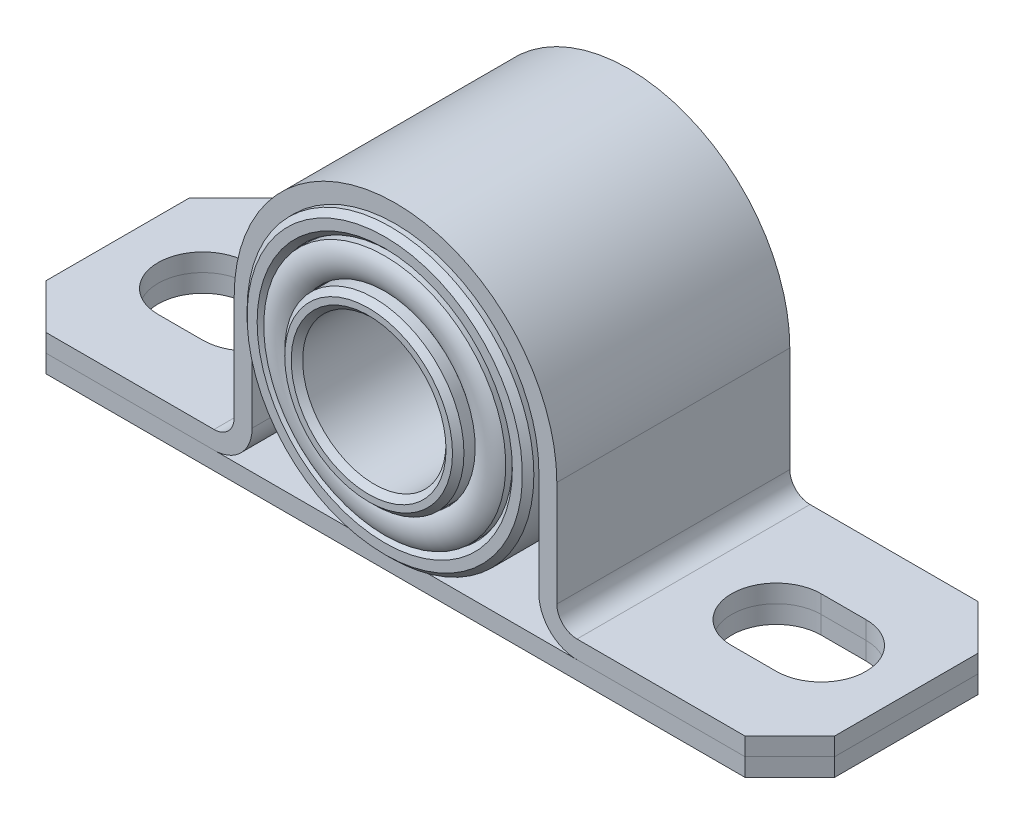
SolidWorks part; units mm, degrees
ref_plane "Front" through (0, 0, 0) normal (0, 0, 1) x (1, 0, 0)
ref_plane "Top" through (0, 0, 0) normal (0, 1, 0) x (1, 0, 0)
ref_plane "Right" through (0, 0, 0) normal (1, 0, 0) x (0, 0, -1)
sketch "Sketch1" plane through (0, 0, 0) normal (0, 1, 0) x (1, 0, 0)
  line L0 (-34.925, -10.3188) -> (34.925, 10.3187) construction
  line L1 (-34.925, -10.3188) -> (34.925, -10.3188)
  line L2 (-34.925, -10.3188) -> (-34.925, 10.3187)
  line L3 (-34.925, 10.3187) -> (34.925, 10.3187)
  line L4 (34.925, -10.3188) -> (34.925, 10.3187)
  line L5 (-27.3844, 0) -> (-23.4156, 0) construction
  line L6 (-23.4156, 0) -> (23.4156, 0) construction
  line L7 (23.4156, 0) -> (27.3844, 0) construction
  line L8 (-27.3844, -3.9688) -> (-23.4156, -3.9688)
  line L9 (23.4156, -3.9688) -> (27.3844, -3.9688)
  line L10 (-27.3844, 3.9688) -> (-23.4156, 3.9688)
  line L11 (23.4156, 3.9688) -> (27.3844, 3.9688)
  arc A0 (-27.3844, -3.9688) -> (-27.3844, 3.9688) centre (-27.3844, 0) cw
  arc A1 (-23.4156, -3.9688) -> (-23.4156, 3.9688) centre (-23.4156, 0) ccw
  arc A2 (23.4156, -3.9688) -> (23.4156, 3.9688) centre (23.4156, 0) cw
  arc A3 (27.3844, -3.9688) -> (27.3844, 3.9688) centre (27.3844, 0) ccw
  point P19 (-25.4, -3.9688)
  point P20 (25.4, -3.9688)
  dimension "Overall Length" = 69.85
  dimension "Mount Width" = 20.6375
  dimension "Hole Width" = 7.9375
  dimension "Hole Length" = 11.9062
  dimension "Hole Centers" = 50.8
extrude "Extrude1" add sketch "Sketch1" along normal blind 1.5875
sketch "Sketch2" plane through (0, 0, 0) normal (0, 0, 1) x (1, 0, 0)
  line L0 (-34.925, 1.5875) -> (-16.0734, 1.5875)
  line L1 (-12.7, 4.9609) -> (-12.7, 14.2875)
  line L2 (12.7, 14.2875) -> (12.7, 4.9609)
  line L3 (16.0734, 1.5875) -> (34.925, 1.5875)
  line L6 (-34.925, 1.5875) -> (-34.925, 3.175)
  line L7 (-34.925, 3.175) -> (-16.0734, 3.175)
  line L8 (-14.2875, 4.9609) -> (-14.2875, 14.2875)
  line L9 (14.2875, 14.2875) -> (14.2875, 4.9609)
  line L10 (16.0734, 3.175) -> (34.925, 3.175)
  line L11 (34.925, 3.175) -> (34.925, 1.5875)
  line L12 (-34.925, 1.5875) -> (-34.925, 0) construction
  line L13 (34.925, 1.5875) -> (34.925, 0) construction
  line L14 (-34.925, 1.5875) -> (34.925, 1.5875) construction
  line L15 (0, 0) -> (0, 28.575) construction
  line L16 (0, 28.575) -> (62.3285, 28.575) construction
  arc A0 (-12.7, 14.2875) -> (12.7, 14.2875) centre (0, 14.2875) cw
  arc A1 (-14.2875, 14.2875) -> (14.2875, 14.2875) centre (0, 14.2875) cw
  arc A2 (14.2875, 4.9609) -> (16.0734, 3.175) centre (16.0734, 4.9609) ccw
  arc A3 (-14.2875, 4.9609) -> (-16.0734, 3.175) centre (-16.0734, 4.9609) cw
  arc A4 (-12.7, 4.9609) -> (-16.0734, 1.5875) centre (-16.0734, 4.9609) cw
  arc A5 (12.7, 4.9609) -> (16.0734, 1.5875) centre (16.0734, 4.9609) ccw
  dimension "D2" = 1.7859
  dimension "Height" = 28.575
  dimension "Center" = 14.2875
extrude "Extrude2" add sketch "Sketch2" along normal up to surface and the other way up to surface separate body up to face at (0, 0.7937, 10.3188) other way up to face at (0, 0.7937, -10.3187)
sketch "Sketch3" plane through (0, 0, 0) normal (0, 1, 0) x (1, 0, 0)
  line L0 (23.4156, -3.9688) -> (27.3844, -3.9688) construction
  line L1 (23.4156, 3.9688) -> (27.3844, 3.9688) construction
  line L2 (-27.3844, -3.9688) -> (-23.4156, -3.9688) construction
  line L3 (-27.3844, 3.9688) -> (-23.4156, 3.9688) construction
  line L4 (23.4156, -3.9688) -> (27.3844, -3.9688)
  line L5 (23.4156, 3.9688) -> (27.3844, 3.9688)
  line L6 (-27.3844, -3.9688) -> (-23.4156, -3.9688)
  line L7 (-27.3844, 3.9688) -> (-23.4156, 3.9688)
  arc A0 (23.4156, 3.9688) -> (23.4156, -3.9688) centre (23.4156, 0) ccw construction
  arc A1 (27.3844, -3.9688) -> (27.3844, 3.9688) centre (27.3844, 0) ccw construction
  arc A2 (-27.3844, 3.9688) -> (-27.3844, -3.9688) centre (-27.3844, 0) ccw construction
  arc A3 (-23.4156, -3.9688) -> (-23.4156, 3.9688) centre (-23.4156, 0) ccw construction
  arc A4 (23.4156, 3.9688) -> (23.4156, -3.9688) centre (23.4156, 0) ccw
  arc A5 (27.3844, -3.9688) -> (27.3844, 3.9688) centre (27.3844, 0) ccw
  arc A6 (-27.3844, 3.9688) -> (-27.3844, -3.9688) centre (-27.3844, 0) ccw
  arc A7 (-23.4156, -3.9688) -> (-23.4156, 3.9688) centre (-23.4156, 0) ccw
extrude "Cut-Extrude1" cut sketch "Sketch3" along normal through all
sketch "Sketch4" plane through (0, 0, 0) normal (1, 0, 0) x (0, 0, -1)
  line L0 (0, 26.9875) -> (-11.2713, 26.9875)
  line L1 (-11.2713, 22.225) -> (-12.7, 22.225)
  line L2 (-11.2713, 26.9875) -> (-11.2713, 25.0825)
  line L3 (-11.2713, 25.0825) -> (-10.5092, 25.0825)
  line L4 (-12.7, 20.6375) -> (0, 20.6375)
  line L5 (0, 20.6375) -> (0, 26.9875)
  line L6 (0, 14.2875) -> (-12.7, 14.2875) construction
  line L7 (10.3187, 26.9875) -> (-10.3188, 26.9875) construction
  line L8 (10.3187, 26.9875) -> (-10.3188, 26.9875) construction
  line L9 (10.3187, 28.575) -> (-10.3188, 28.575) construction
  line L10 (10.3187, 28.575) -> (-10.3188, 28.575) construction
  line L11 (-10.3188, 28.575) -> (-10.3188, 26.9875) construction
  line L12 (-10.5092, 25.0825) -> (-10.5092, 25.0063)
  line L13 (0, 14.2875) -> (0, 20.6375) construction
  line L14 (-10.5092, 25.0063) -> (-11.2712, 25.0063)
  line L15 (-12.7, 22.225) -> (-12.7, 20.6375)
  line L16 (-11.2713, 22.225) -> (-10.5092, 22.225)
  line L17 (-10.5092, 22.225) -> (-10.5092, 22.3012)
  line L18 (-10.5092, 22.3012) -> (-11.2712, 22.3012)
  line L19 (-10.3188, 28.575) -> (-10.3188, 14.2875) construction
  line L20 (-11.7475, 23.6537) -> (-11.2713, 23.6537) construction
  arc A0 (-11.2712, 25.0063) -> (-11.2712, 22.3012) centre (-9.5888, 23.6537) ccw
  dimension "Shaft Dia" = 12.7
  dimension "Flange Dia" = 15.875
  dimension "Bearing Width" = 25.4
  dimension "D1" = 4.7625
  dimension "D2" = 0.0762
  dimension "D3" = 0.762
  dimension "D4" = 2.3812
  dimension "D5" = 0.9525
  dimension "D6" = 2.8575
  dimension "D7" = 0.4762
revolve "Revolve1" add sketch "Sketch4" angle 360 about L6
chamfer "Chamfer3" distance 0.508 angle 45 4 edges at (0, 26.9875, 11.2713) (0, 25.0825, 11.2713) (0, 20.6375, 12.7) (0, 22.225, 12.7)
mirror "Mirror2" about plane through (0, 0, 0) normal (0, 0, 1) of bodies 111
chamfer "Chamfer1" distance 3.9688 angle 45 4 edges at (-34.925, 0.7937, -10.3187) (-34.925, 0.7937, 10.3188) (34.925, 0.7937, -10.3187) (34.925, 0.7937, 10.3188)
chamfer "Chamfer2" distance 3.9688 angle 45 4 edges at (34.925, 2.3812, 10.3188) (34.925, 2.3812, -10.3187) (-34.925, 2.3812, 10.3188) (-34.925, 2.3812, -10.3187)
sketch "Sketch5" plane through (0, 0, 0) normal (0, -1, 0) x (1, 0, 0)
  line L0 (-34.925, 6.35) -> (-30.9563, 10.3188)
  line L1 (-30.9563, 10.3188) -> (30.9562, 10.3188) construction
  line L2 (-30.9563, 10.3188) -> (-34.925, 6.35) construction
  line L3 (-30.9563, 10.3188) -> (30.9562, 10.3188)
  line L4 (30.9562, 10.3188) -> (34.925, 6.35)
  line L5 (34.925, 6.35) -> (34.925, -6.35)
  line L6 (34.925, -6.35) -> (30.9562, -10.3187)
  line L7 (30.9562, -10.3187) -> (-30.9562, -10.3187)
  line L8 (-30.9562, -10.3187) -> (-34.925, -6.35)
  line L9 (-34.925, -6.35) -> (-34.925, 6.35)
  line L10 (-27.3844, 3.9688) -> (-23.4156, 3.9688)
  line L11 (-27.3844, -3.9688) -> (-23.4156, -3.9688)
  line L12 (23.4156, 3.9688) -> (27.3844, 3.9688)
  line L13 (23.4156, -3.9688) -> (27.3844, -3.9688)
  arc A0 (-27.3844, 3.9688) -> (-27.3844, -3.9688) centre (-27.3844, 0) ccw
  arc A1 (-23.4156, 3.9688) -> (-23.4156, -3.9688) centre (-23.4156, 0) cw
  arc A2 (23.4156, 3.9688) -> (23.4156, -3.9688) centre (23.4156, 0) ccw
  arc A3 (27.3844, 3.9688) -> (27.3844, -3.9688) centre (27.3844, 0) cw
  dimension "D1" = 3.9688
  dimension "D2" = 3.9688
  dimension "D3" = 3.9688
equation "\"D2@Sketch2\"= \"Center@Sketch2\" / 8"
equation "\"D1@Chamfer2\"=\"D1@Chamfer1\""
equation "\"D1@Chamfer1\"=\"Hole Width@Sketch1\"/2"
equation "\"D5@Sketch4\"=\"D4@Sketch4\"*.4"
equation "\"D6@Sketch4\"=\"D1@Sketch4\"*.6"
equation "\"D7@Sketch4\"=\"D5@Sketch4\"/2"
